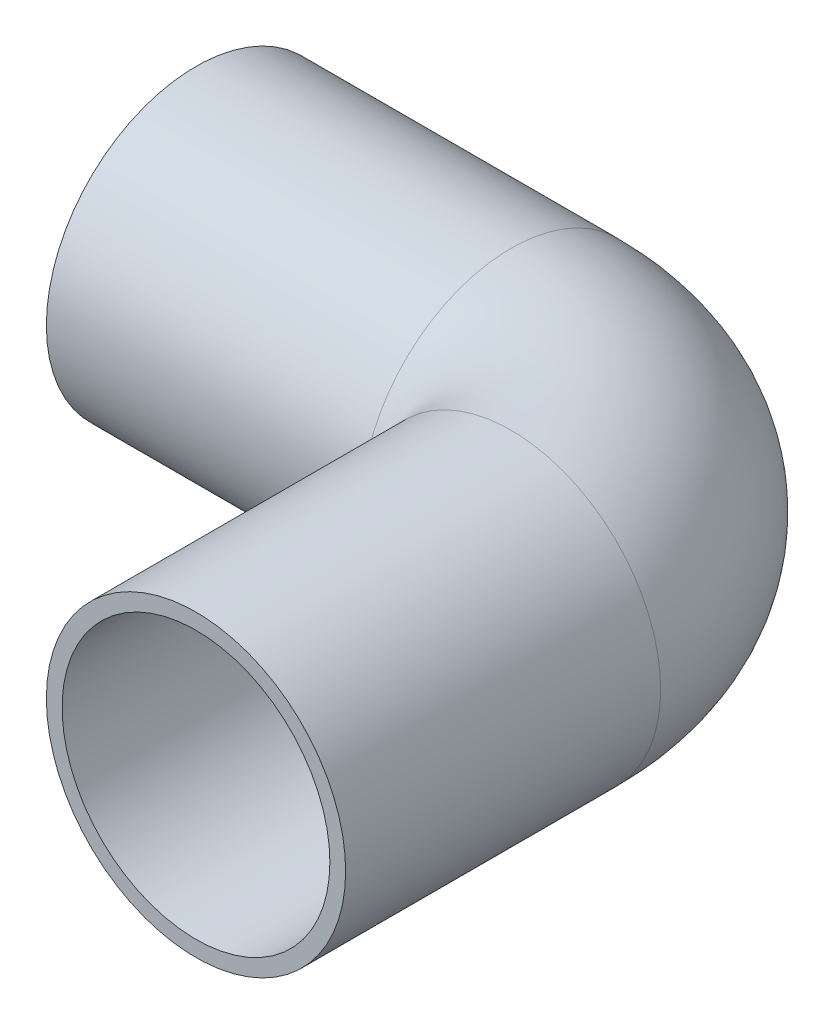
SolidWorks part; units mm, degrees
ref_plane "Front Plane" through (0, 0, 0) normal (0, 0, 1) x (1, 0, 0)
ref_plane "Top Plane" through (0, 0, 0) normal (0, 1, 0) x (1, 0, 0)
ref_plane "Right Plane" through (0, 0, 0) normal (1, 0, 0) x (0, 0, -1)
sketch "Sketch1" plane through (0, 0, 0) normal (0, 0, 1) x (1, 0, 0)
  circle A0 centre (0, 0) radius 17
  circle A1 centre (0, 0) radius 19
  dimension "D1" = 34
  dimension "D2" = 2
sketch "Sketch2" plane through (0, 0, 0) normal (0, 1, 0) x (1, 0, 0)
  line L0 (0, 0) -> (0, 40)
  line L1 (-20, 60) -> (-60, 60)
  arc A0 (0, 40) -> (-20, 60) centre (-20, 40) ccw
  point P6 (0, 60)
  dimension "D2" = 20
  dimension "D1" = 60
sweep "Sweep1" add profiles "Sketch1" path "Sketch2"
